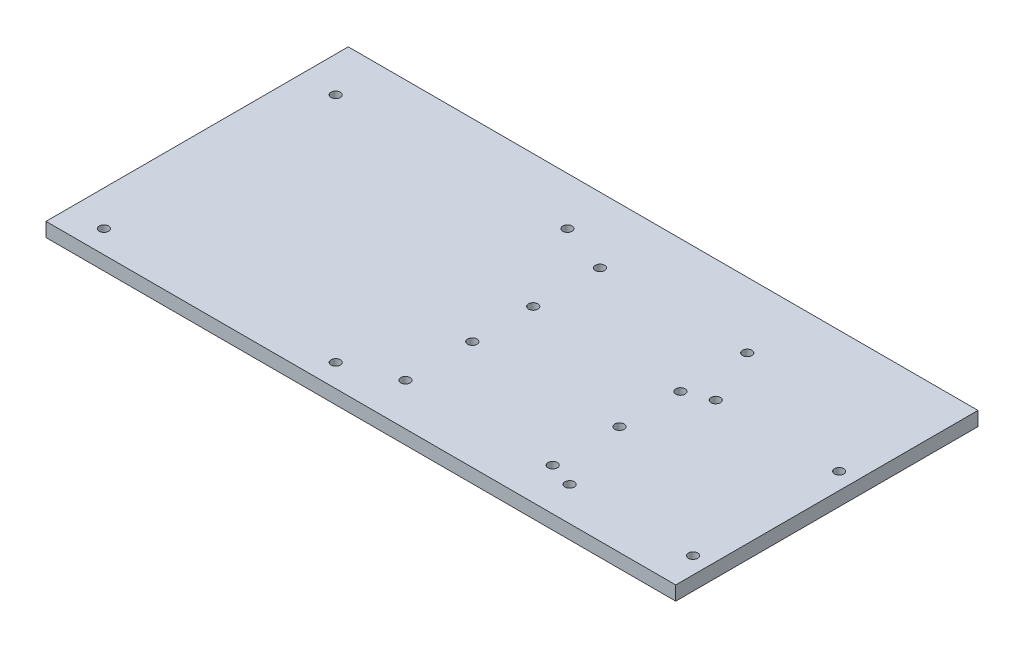
SolidWorks part; units mm, degrees
ref_plane "Front Plane" through (0, 0, 0) normal (0, 0, 1) x (1, 0, 0)
ref_plane "Top Plane" through (0, 0, 0) normal (0, 1, 0) x (1, 0, 0)
ref_plane "Right Plane" through (0, 0, 0) normal (1, 0, 0) x (0, 0, -1)
sketch "Sketch1" plane through (0, 0, 0) normal (0, 1, 0) x (1, 0, 0)
  line L1 (-125, -60) -> (125, -60)
  line L2 (-125, -60) -> (-125, 60)
  line L3 (-125, 60) -> (125, 60)
  line L4 (125, -60) -> (125, 60)
  line L5 (-125, -60) -> (125, 60) construction
  line L6 (-125, 60) -> (125, -60) construction
  point P0 (0, 0)
  dimension "D1" = 120
  dimension "D2" = 250
extrude "Boss-Extrude1" add sketch "Sketch1" along normal blind 5.588
hole_wizard "Ø3.0mm Clearance Dowel Hole2" positions "Sketch4" profile "Sketch5" hole size "Ø3.0" standard "ANSI Metric" end condition through all
sketch "Sketch4" plane through (-44.961, 0, -163.6882) normal (0, -1, 0) x (-1, 0, 0)
  point P0 (-45.936, -156.2482)
  point P3 (-25.961, -122.6882)
  point P6 (-45.936, -129.7282)
  point P9 (-45.936, -180.4282)
  point P12 (-45.936, -206.9482)
  point P15 (-25.961, -214.6882)
  point P18 (66.039, -214.6882)
  point P51 (-104.386, -206.9482)
  point P54 (-104.386, -180.4282)
  point P57 (-104.386, -156.2482)
  point P60 (-104.386, -129.7282)
  point P63 (-163.3388, -210.1882)
  point P66 (-163.3388, -152.1882)
  point P69 (-114.3388, -152.1882)
  point P72 (-114.3388, -210.1882)
  point P81 (66.039, -122.6882)
  point P86 (0, 0)
sketch "Sketch5" plane through (0.975, 0, -7.44) normal (1, 0, 0) x (0, 0, -1)
  line L0 (0, 0) -> (0, 5.588)
  line L1 (0, 5.588) -> (1.85, 5.588)
  line L2 (1.85, 5.588) -> (1.85, 0)
  line L3 (1.85, 0) -> (0, 0)
  line L4 (0, -6.35) -> (0, 107.95) construction
  dimension "Thru Hole Dia." = 3.7
  dimension "Thru Hole Depth" = 5.588
